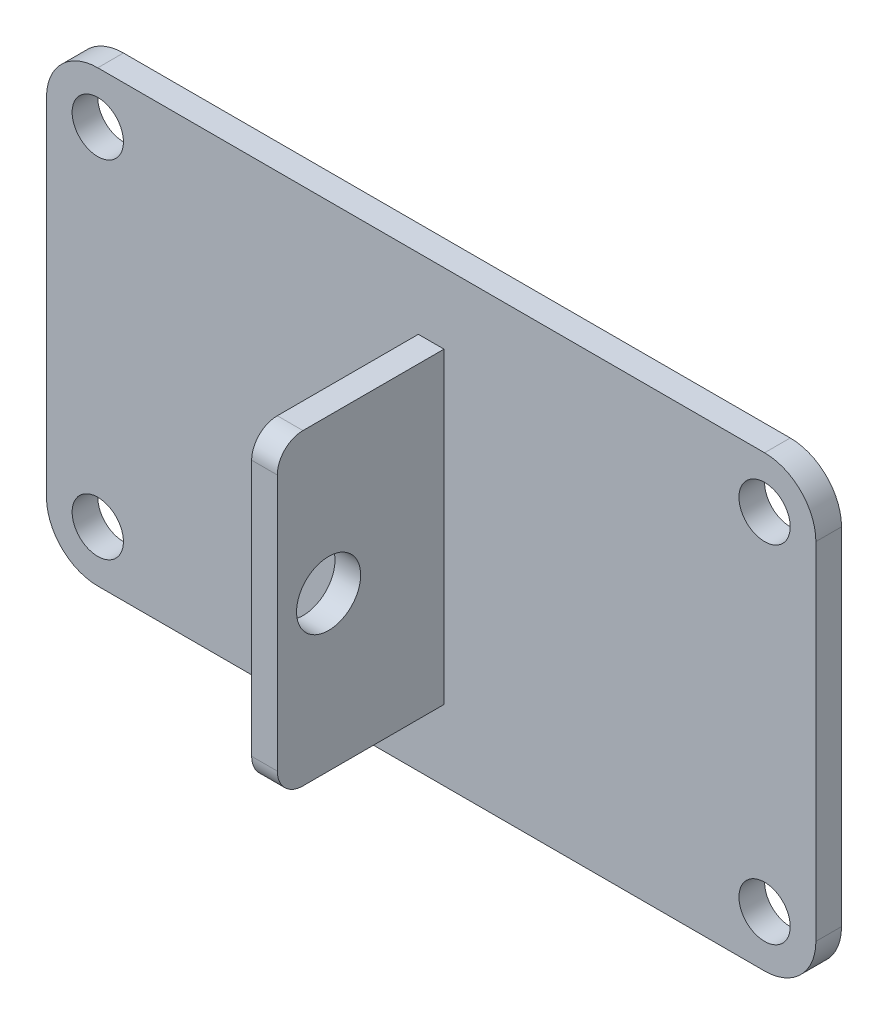
SolidWorks part; units mm, degrees
ref_plane "Płaszczyzna przednia" through (0, 0, 0) normal (0, 0, 1) x (1, 0, 0)
ref_plane "Płaszczyzna górna" through (0, 0, 0) normal (0, 1, 0) x (1, 0, 0)
ref_plane "Płaszczyzna prawa" through (0, 0, 0) normal (1, 0, 0) x (0, 0, -1)
sketch "Szkic1" plane through (0, 0, 0) normal (0, 0, 1) x (1, 0, 0)
  line L1 (-130, 87.5) -> (130, 87.5)
  line L2 (-150, 67.5) -> (-150, -67.5)
  line L3 (-130, -87.5) -> (130, -87.5)
  line L4 (150, 67.5) -> (150, -67.5)
  line L5 (-150, 87.5) -> (150, -87.5) construction
  line L6 (-150, -87.5) -> (150, 87.5) construction
  arc A0 (150, 67.5) -> (130, 87.5) centre (130, 67.5) ccw
  arc A1 (130, -87.5) -> (150, -67.5) centre (130, -67.5) ccw
  arc A2 (-130, -87.5) -> (-150, -67.5) centre (-130, -67.5) cw
  arc A3 (-150, 67.5) -> (-130, 87.5) centre (-130, 67.5) cw
  circle A4 centre (-130, 67.5) radius 10
  circle A5 centre (-130, -67.5) radius 10
  circle A6 centre (130, -67.5) radius 10
  circle A7 centre (130, 67.5) radius 10
  point P0 (0, 0)
  dimension "D1" = 20
  dimension "D4" = 20
  dimension "D5" = 20
  dimension "D6" = 20
  dimension "D7" = 20
  dimension "D2" = 300
  dimension "D3" = 175
extrude "Dodanie-wyciągnięcie1" add sketch "Szkic1" along normal blind 10
sketch "Szkic2" plane through (0, 0, 10) normal (0, 0, 1) x (1, 0, 0)
  line L1 (-5, 60) -> (5, 60)
  line L2 (-5, 60) -> (-5, -60)
  line L3 (-5, -60) -> (5, -60)
  line L4 (5, 60) -> (5, -60)
  line L5 (-5, 60) -> (5, -60) construction
  line L6 (-5, -60) -> (5, 60) construction
  point P0 (0, 0)
  dimension "D1" = 10
  dimension "D2" = 120
extrude "Dodanie-wyciągnięcie2" add sketch "Szkic2" along normal blind 65
fillet "Zaokrąglenie1" radius 10 2 edges at (0, -60, 75) (0, 60, 75)
sketch "Szkic4" plane through (5, 0, 0) normal (1, 0, 0) x (0, 0, -1)
  line L0 (-65, 60) -> (-10, 60) construction
  line L1 (0, -67.5) -> (0, 67.5) construction
  circle A0 centre (-55, 0) radius 12.5
  dimension "D3" = 25
  dimension "D1" = 60
  dimension "D2" = 55
extrude "Wytnij-wyciągnięcie1" cut sketch "Szkic4" against normal blind 65
